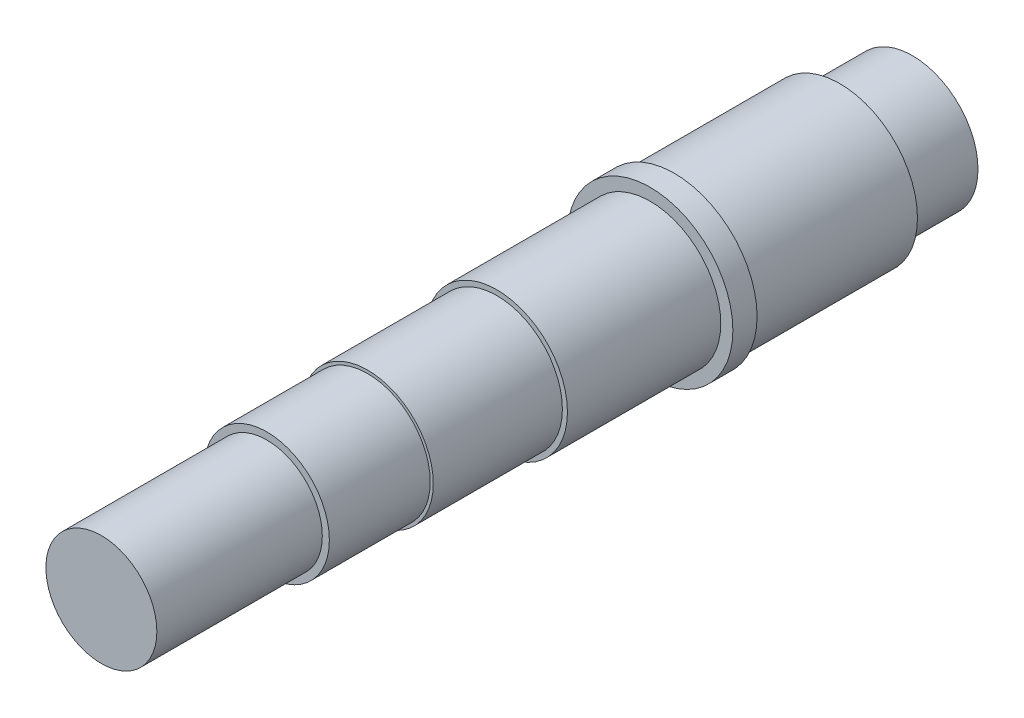
SolidWorks part; units mm, degrees
ref_plane "前视基准面" through (0, 0, 0) normal (0, 0, 1) x (1, 0, 0)
ref_plane "上视基准面" through (0, 0, 0) normal (0, 1, 0) x (1, 0, 0)
ref_plane "右视基准面" through (0, 0, 0) normal (1, 0, 0) x (0, 0, -1)
sketch "草图1" plane through (0, 0, 0) normal (0, 0, 1) x (1, 0, 0)
  circle A0 centre (0, 0) radius 32.5
  dimension "D1" = 65
extrude "凸台-拉伸1" add sketch "草图1" along normal blind 36
sketch "草图2" plane through (0, 0, 36) normal (0, 0, 1) x (1, 0, 0)
  circle A0 centre (0, 0) radius 38.5
  dimension "D1" = 77
extrude "凸台-拉伸2" add sketch "草图2" along normal blind 82
sketch "草图3" plane through (0, 0, 118) normal (0, 0, 1) x (1, 0, 0)
  circle A0 centre (0, 0) radius 41
  dimension "D1" = 82
extrude "凸台-拉伸3" add sketch "草图3" along normal blind 12
sketch "草图4" plane through (0, 0, 130) normal (0, 0, 1) x (1, 0, 0)
  circle A0 centre (0, 0) radius 35
  dimension "D1" = 70
extrude "凸台-拉伸4" add sketch "草图4" along normal blind 76
sketch "草图5" plane through (0, 0, 206) normal (0, 0, 1) x (1, 0, 0)
  circle A0 centre (0, 0) radius 32.5
  dimension "D1" = 65
extrude "凸台-拉伸5" add sketch "草图5" along normal blind 64
sketch "草图6" plane through (0, 0, 270) normal (0, 0, 1) x (1, 0, 0)
  circle A0 centre (0, 0) radius 31
  dimension "D1" = 62
extrude "凸台-拉伸6" add sketch "草图6" along normal blind 50
sketch "草图7" plane through (0, 0, 320) normal (0, 0, 1) x (1, 0, 0)
  circle A0 centre (0, 0) radius 27.5
  dimension "D1" = 55
extrude "凸台-拉伸7" add sketch "草图7" along normal blind 82
